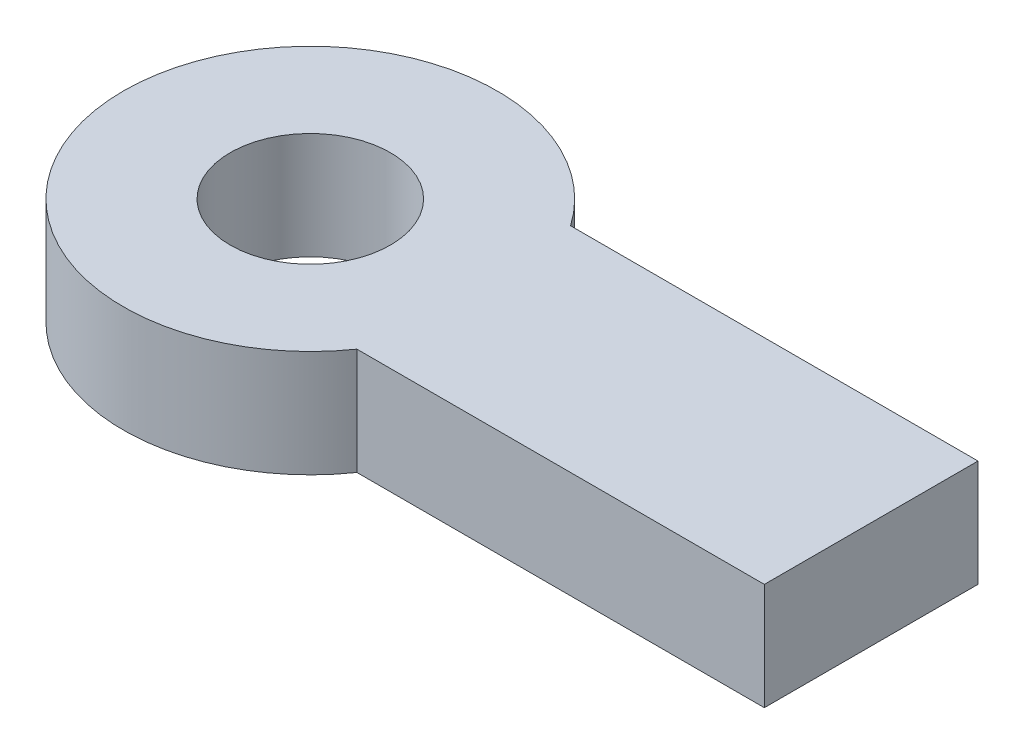
SolidWorks part; units mm, degrees
ref_plane "Płaszczyzna przednia" through (0, 0, 0) normal (0, 0, 1) x (1, 0, 0)
ref_plane "Płaszczyzna górna" through (0, 0, 0) normal (0, 1, 0) x (1, 0, 0)
ref_plane "Płaszczyzna prawa" through (0, 0, 0) normal (1, 0, 0) x (0, 0, -1)
sketch "Szkic1" plane through (0, 0, 0) normal (0, 1, 0) x (1, 0, 0)
  line L0 (3.5, 0) -> (10.5, 0) construction
  line L1 (3.5, 2) -> (10.5, 2)
  line L3 (3.5, -2) -> (10.5, -2)
  line L4 (10.5, 2) -> (10.5, -2)
  line L5 (3.5, 0) -> (0, 0) construction
  line L7 (3.5, 2) -> (2.8723, 2)
  line L9 (3.5, -2) -> (2.8723, -2)
  circle A0 centre (0, 0) radius 1.5
  arc A1 (2.8723, 2) -> (2.8723, -2) centre (0, 0) ccw
  dimension "D1" = 3
  dimension "D2" = 7
  dimension "D4" = 7
  dimension "D3" = 4
extrude "Dodanie-wyciągnięcie1" add sketch "Szkic1" along normal blind 2
